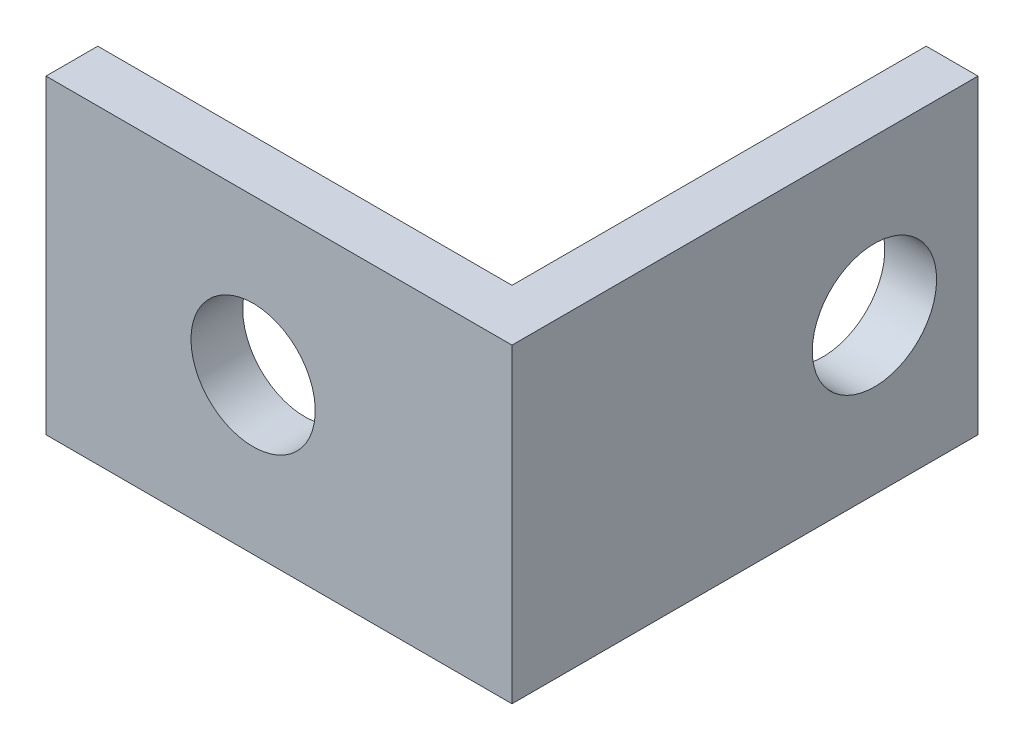
SolidWorks part; units mm, degrees
ref_plane "Front Plane" through (0, 0, 0) normal (0, 0, 1) x (1, 0, 0)
ref_plane "Top Plane" through (0, 0, 0) normal (0, 1, 0) x (1, 0, 0)
ref_plane "Right Plane" through (0, 0, 0) normal (1, 0, 0) x (0, 0, -1)
sketch "Sketch3" plane through (0, 0, 0) normal (0, 1, 0) x (1, 0, 0)
  line L0 (0, 0) -> (22.5, 0)
  line L1 (22.5, 0) -> (22.5, 22.5)
  line L2 (22.5, 22.5) -> (20, 22.5)
  line L3 (20, 22.5) -> (20, 2.5)
  line L4 (20, 2.5) -> (0, 2.5)
  line L5 (0, 2.5) -> (0, 0)
  dimension "D1" = 2.5
  dimension "D2" = 20
extrude "Boss-Extrude2" add sketch "Sketch3" along normal blind 15
sketch "Sketch4" plane through (0, 0, -2.5) normal (0, 0, -1) x (-1, 0, 0)
  line L0 (-20, 15) -> (0, 0) construction
  circle A0 centre (-10, 7.5) radius 3
  dimension "D1" = 6
extrude "Cut-Extrude2" cut sketch "Sketch4" against normal through all
sketch "Sketch7" plane through (20, 0, 0) normal (-1, 0, 0) x (0, 0, 1)
  line L0 (-22.5, 15) -> (-22.5, 0) construction
  line L1 (-22.5, 0) -> (-17.5, 7.5) construction
  line L2 (-17.5, 7.5) -> (-22.5, 15) construction
  circle A1 centre (-17.5, 7.5) radius 3
  point P1 (0, 0)
  dimension "D2" = 6
  dimension "D1" = 5
extrude "Cut-Extrude4" cut sketch "Sketch7" against normal through all
equation "\"pulleybolt\"=0.6"
equation "\"D2@Sketch7\"=\"pulleybolt\""
